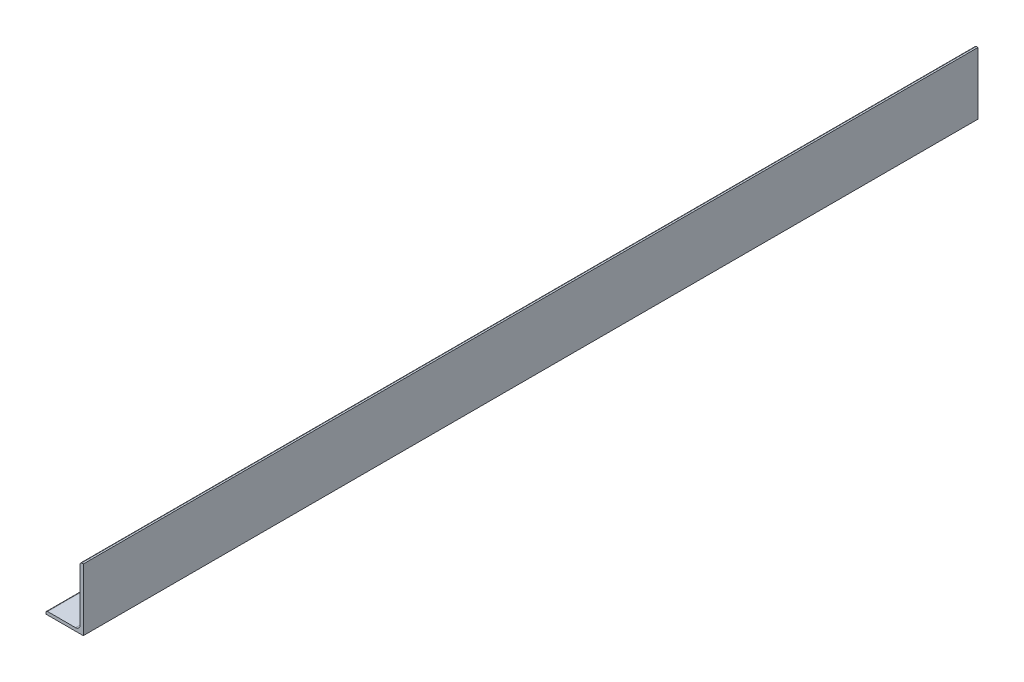
SolidWorks part; units mm, degrees
ref_plane "Front Plane" through (0, 0, 0) normal (0, 0, 1) x (1, 0, 0)
ref_plane "Top Plane" through (0, 0, 0) normal (0, 1, 0) x (1, 0, 0)
ref_plane "Right Plane" through (0, 0, 0) normal (1, 0, 0) x (0, 0, -1)
sketch "Sketch0" plane through (0, 0, 0) normal (0, 0, 1) x (1, 0, 0)
  line L0 (-19.05, -31.75) -> (19.05, -31.75)
  line L1 (19.05, -31.75) -> (19.05, 31.75)
  line L2 (19.05, 0) -> (0, 0) construction
  line L3 (0, 0) -> (0, -31.75) construction
  line L4 (15.875, -23.7998) -> (15.875, 31.75) construction
  line L5 (11.0998, -28.575) -> (-19.05, -28.575) construction
  arc A0 (15.875, -23.7998) -> (11.0998, -28.575) centre (11.0998, -23.7998) cw
  point P3 (14.4764, -27.1764)
  dimension "Inside Corner Radius" = 4.7752
  dimension "Outside Height" = 63.5
  dimension "Inside Height" = 60.325
  dimension "Inside Width" = 34.925
  dimension "Wall Thickness" = 3.175
  dimension "D1" = 3.175
  dimension "Outside Width" = 38.1
sketch "Sketch1" plane through (0, 0, 0) normal (1, 0, 0) x (0, 0, -1)
  line L0 (457.2, 0) -> (-457.2, 0)
  point P4 (0, 0)
  dimension "Length" = 914.4
sketch "Sketch2" plane through (0, 0, 0) normal (0, 0, 1) x (1, 0, 0)
  line L0 (-19.05, -31.75) -> (19.05, -31.75)
  line L1 (19.05, -31.75) -> (19.05, 31.75)
  line L2 (19.05, 31.75) -> (15.875, 31.75) construction
  line L3 (15.875, 30.1625) -> (15.875, -23.7998)
  line L4 (11.0998, -28.575) -> (-17.4625, -28.575)
  line L5 (-19.05, -31.75) -> (-19.05, -28.575) construction
  line L6 (17.4625, 31.75) -> (19.05, 31.75)
  line L7 (-19.05, -30.1625) -> (-19.05, -31.75)
  line L8 (19.05, 0) -> (0, 0) construction
  line L9 (0, 0) -> (0, -31.75) construction
  arc A0 (15.875, 30.1625) -> (17.4625, 31.75) centre (17.4625, 30.1625) cw
  arc A1 (-19.05, -30.1625) -> (-17.4625, -28.575) centre (-17.4625, -30.1625) cw
  arc A2 (15.875, -23.7998) -> (11.0998, -28.575) centre (11.0998, -23.7998) cw
  dimension "Inside Radius" = 4.7752
  dimension "Height" = 63.5
  dimension "Width" = 38.1
  dimension "Thickness" = 3.175
extrude "Boss-Extrude1" add sketch "Sketch2" along normal mid plane 914.4
sketch "Break Locations" plane through (0, 0, 0) normal (1, 0, 0) x (0, 0, -1)
  line L0 (-392.43, 0) -> (392.43, 0)
  line L1 (-457.2, -31.75) -> (-457.2, 31.75) construction
  line L2 (457.2, -31.75) -> (457.2, 31.75) construction
  point P0 (-403.225, 0)
  point P1 (403.225, 0)
  point P10 (0, 0)
  point P11 (392.43, 0)
  point P13 (-392.43, 0)
  dimension "D1" = 53.975
  dimension "D2" = 53.975
  dimension "D3" = 64.77
equation "\"D1@Break Locations\" = .85 * \"Height@Sketch2\""
equation "\"D2@Break Locations\"=\"D1@Break Locations\""
equation "\"Thickness@Sketch2\"=\"wall thickness@sketch0\""
equation "\"Height@Sketch2\"=\"outside height@sketch0\""
equation "\"Width@Sketch2\"=\"outside width@sketch0\""
equation "\"Inside Radius@Sketch2\"=\"inside corner radius@sketch0\""
equation "\"Length@Boss-Extrude1\"=\"length@sketch1\""
equation "\"D3@Break Locations\"=\"D2@Break Locations\"*1.2"
equation "\"D1@Sketch0\"=\"Wall Thickness@Sketch0\""
